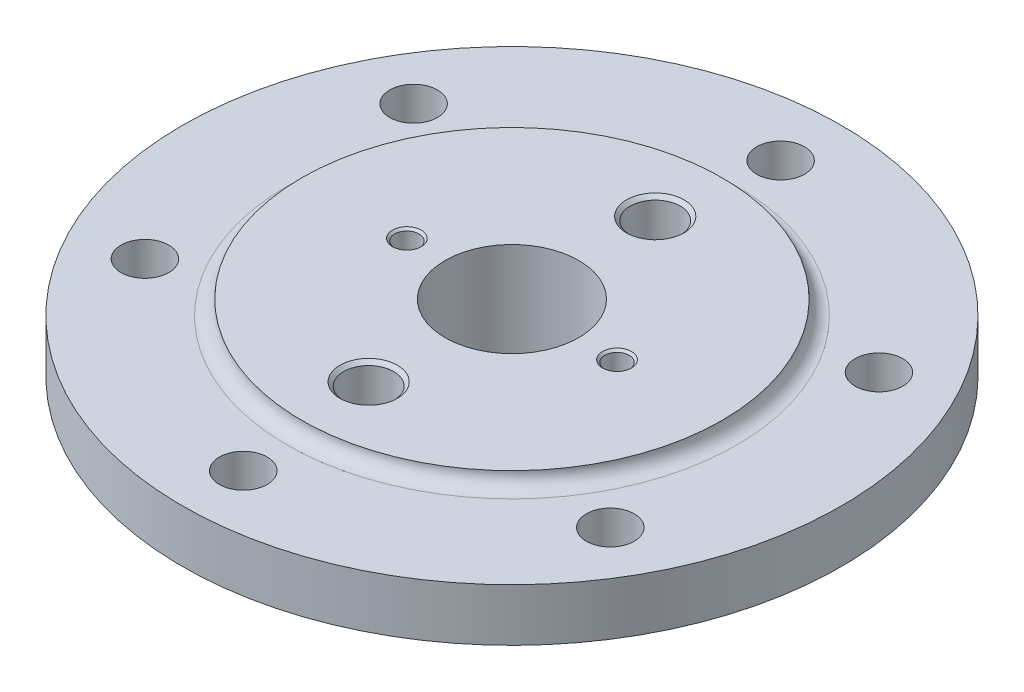
SolidWorks part; units mm, degrees
ref_plane "Front Plane" through (0, 0, 0) normal (0, 0, 1) x (1, 0, 0)
ref_plane "Top Plane" through (0, 0, 0) normal (0, 1, 0) x (1, 0, 0)
ref_plane "Right Plane" through (0, 0, 0) normal (1, 0, 0) x (0, 0, -1)
sketch "Sketch1" plane through (0, 0, 0) normal (0, 0, 1) x (1, 0, 0)
  line L0 (-29.6935, 26.3629) -> (-29.6935, -39.9113) construction
  line L1 (-73.2742, -6.7742) -> (29.8065, -6.7742) construction
  line L2 (5.3065, -6.7742) -> (-15.6935, -6.7742)
  line L3 (-15.6935, -6.7742) -> (-15.6935, 10.1429)
  line L4 (-15.6935, 10.1429) -> (-1.6935, 18.2258)
  line L5 (-1.6935, 18.2258) -> (-1.6935, 74.2258)
  line L6 (-1.6935, 74.2258) -> (58.3065, 74.2258)
  line L7 (64.3065, 68.2258) -> (108.3065, 68.2258)
  line L8 (108.3065, 68.2258) -> (108.3065, 46.2258)
  line L9 (108.3065, 46.2258) -> (51.3065, 46.2258)
  line L10 (51.3065, 46.2258) -> (51.3065, 40.2258)
  line L11 (51.3065, 40.2258) -> (5.3065, -6.7742)
  arc A0 (58.3065, 74.2258) -> (64.3065, 68.2258) centre (64.3065, 74.2258) ccw
  dimension "D1" = 14
  dimension "D2" = 35
  dimension "D3" = 47
  dimension "D4" = 6
  dimension "D5" = 22
  dimension "D6" = 6
  dimension "D7" = 138
  dimension "D8" = 88
  dimension "D9" = 50
  dimension "D10" = 60
  dimension "D11" = 28
  dimension "D12" = 81
revolve "Revolve1" add sketch "Sketch1" angle 360 about L0
sketch "Sketch2" plane through (0, 68.2258, 0) normal (0, 1, 0) x (1, 0, 0)
  line L0 (-29.6935, 0) -> (-29.6935, 112.5) construction
  circle A0 centre (-29.6935, 112.5) radius 10
  circle A1 centre (67.7343, 56.25) radius 10
  circle A2 centre (67.7343, -56.25) radius 10
  circle A3 centre (-29.6935, -112.5) radius 10
  circle A4 centre (-127.1214, -56.25) radius 10
  circle A5 centre (-127.1214, 56.25) radius 10
  point P16 (-29.6935, 0)
  dimension "D2" = 20
  dimension "D1" = 112.5
  dimension "D3" = 6
extrude "Cut-Extrude1" cut sketch "Sketch2" against normal through all
hole_wizard "M24 Tapped Hole1" positions "Sketch4" profile "Sketch3" tap size "M24" standard "ISO"
sketch "Sketch4" plane through (0, 74.2258, 0) normal (0, 1, 0) x (1, 0, 0)
  line L0 (-29.6935, 0) -> (-29.6935, -60) construction
  line L2 (-29.6935, 0) -> (-29.6935, 60) construction
  point P1 (-29.6935, -60)
  point P7 (-29.6935, 60)
  dimension "D1" = 60
cosmetic thread "Hole Thread1" parameters "D1"=24, "D2"=24
cosmetic thread "Hole Thread2" parameters "D1"=24, "D2"=24
sketch "Sketch3" plane through (-29.6935, 74.2258, -60) normal (1, 0, 0) x (0, 0, 1)
  line L0 (0, 0) -> (0, 33.309)
  line L1 (0, 33.309) -> (10.5, 27)
  line L2 (10.5, 27) -> (10.5, 1.525)
  line L3 (10.5, 1.525) -> (12.025, 0)
  line L5 (12.025, 0) -> (0, 0)
  line L6 (-10.5, 1.525) -> (-12.025, 0) construction
  line L10 (0, 33.309) -> (-10.5, 27) construction
  line L11 (0, -6.35) -> (0, 107.95) construction
  dimension "Tap Drill Dia." = 21
  dimension "Tap Drill Depth" = 27
  dimension "Near C'Sink Dia." = 24.05
  dimension "Near C'Sink Angle" = 90
  dimension "Drill Angle" = 118
hole_wizard "M12 Tapped Hole1" positions "Sketch6" profile "Sketch7" tap size "M12" standard "ISO"
sketch "Sketch6" plane through (0, 74.2258, 0) normal (0, 1, 0) x (1, 0, 0)
  line L0 (-29.6935, 0) -> (-73.6935, 0) construction
  line L2 (-29.6935, 0) -> (14.3065, 0) construction
  point P2 (-73.6935, 0)
  point P9 (14.3065, 0)
  dimension "D1" = 44
sketch "Sketch7" plane through (14.3065, 74.2258, 0) normal (1, 0, 0) x (0, 0, 1)
  line L0 (0, 0) -> (0, 20.3144)
  line L1 (0, 20.3144) -> (5.1, 17.25)
  line L2 (5.1, 17.25) -> (5.1, 0.925)
  line L3 (5.1, 0.925) -> (6.025, 0)
  line L5 (6.025, 0) -> (0, 0)
  line L6 (-5.1, 0.925) -> (-6.025, 0) construction
  line L10 (0, 20.3144) -> (-5.1, 17.25) construction
  line L11 (0, -6.35) -> (0, 107.95) construction
  dimension "Tap Drill Dia." = 10.2
  dimension "Tap Drill Depth" = 17.25
  dimension "Near C'Sink Dia." = 12.05
  dimension "Near C'Sink Angle" = 90
  dimension "Drill Angle" = 118
cosmetic thread "Hole Thread3" parameters "D1"=12, "D2"=12
cosmetic thread "Hole Thread4" parameters "D1"=12, "D2"=12
